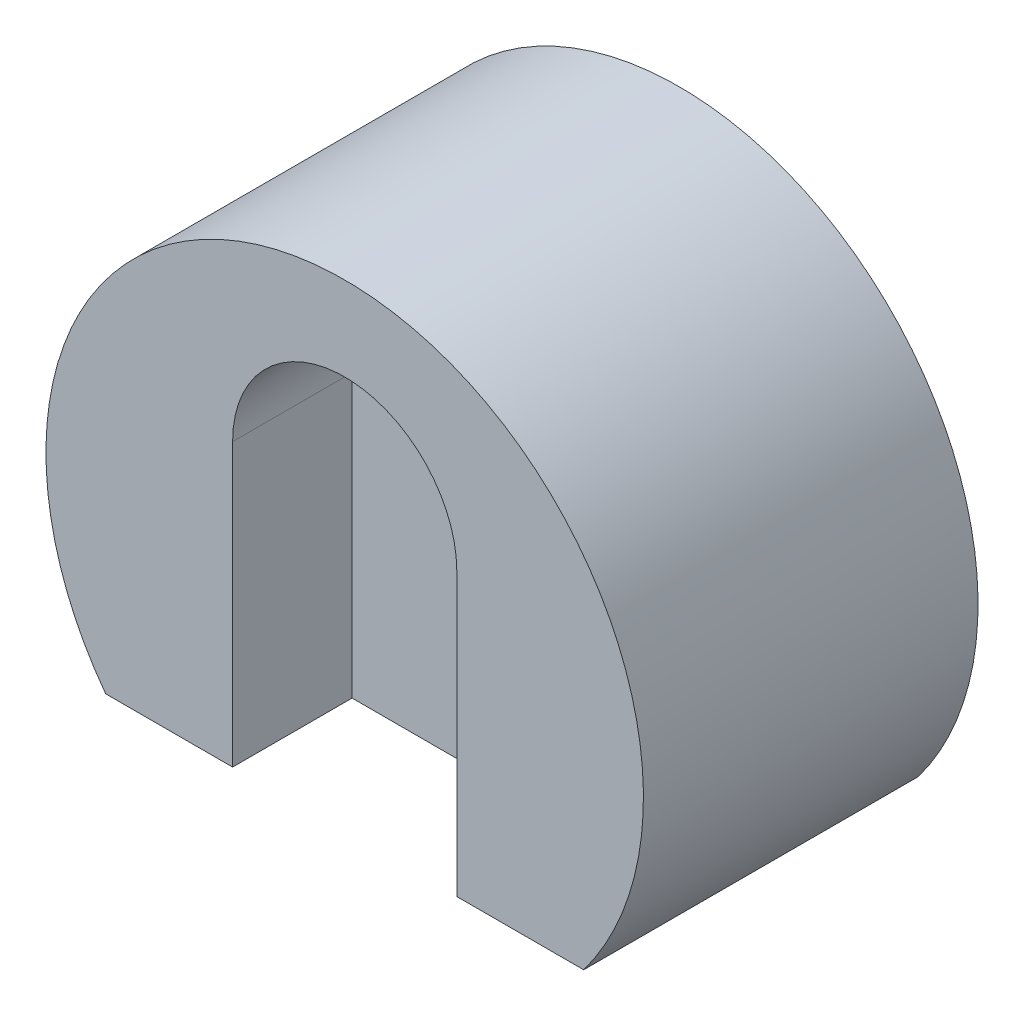
SolidWorks part; units mm, degrees
ref_plane "Ebene vorne" through (0, 0, 0) normal (0, 0, 1) x (1, 0, 0)
ref_plane "Ebene oben" through (0, 0, 0) normal (0, 1, 0) x (1, 0, 0)
ref_plane "Ebene rechts" through (0, 0, 0) normal (1, 0, 0) x (0, 0, -1)
sketch "Skizze1" plane through (0, 0, 0) normal (0, 0, 1) x (1, 0, 0)
  line L0 (-4, -3) -> (4, -3)
  line L1 (0, 0) -> (0, -3) construction
  line L2 (55, 0) -> (-55, 0) construction
  arc A0 (4, -3) -> (-4, -3) centre (0, 0) ccw
  dimension "D1" = 10
  dimension "D2" = 3
extrude "Aufsatz-Linear austragen1" add sketch "Skizze1" against normal blind 5.6
sketch "Skizze2" plane through (0, 0, 0) normal (0, 0, 1) x (1, 0, 0)
  line L0 (-1.8763, -1.7177) -> (-1.8763, -3)
  line L1 (-1.8763, -1.7177) -> (1.8763, -1.7177) construction
  line L2 (-1.8763, -1.7177) -> (-1.8763, 1.7177)
  line L3 (-1.8763, 1.7177) -> (1.8763, 1.7177) construction
  line L4 (1.8763, -1.7177) -> (1.8763, 1.7177)
  line L5 (-1.8763, -1.7177) -> (1.8763, 1.7177) construction
  line L6 (-1.8763, 1.7177) -> (1.8763, -1.7177) construction
  line L7 (-4, -3) -> (4, -3) construction
  line L8 (-1.8763, -3) -> (1.8763, -3)
  line L9 (1.8763, -3) -> (1.8763, -1.7177)
  arc A0 (-1.8763, 1.7177) -> (1.8763, 1.7177) centre (0, 1.7177) cw
  point P0 (0, 0)
extrude "Schnitt-Linear austragen1" cut sketch "Skizze2" against normal blind 2
